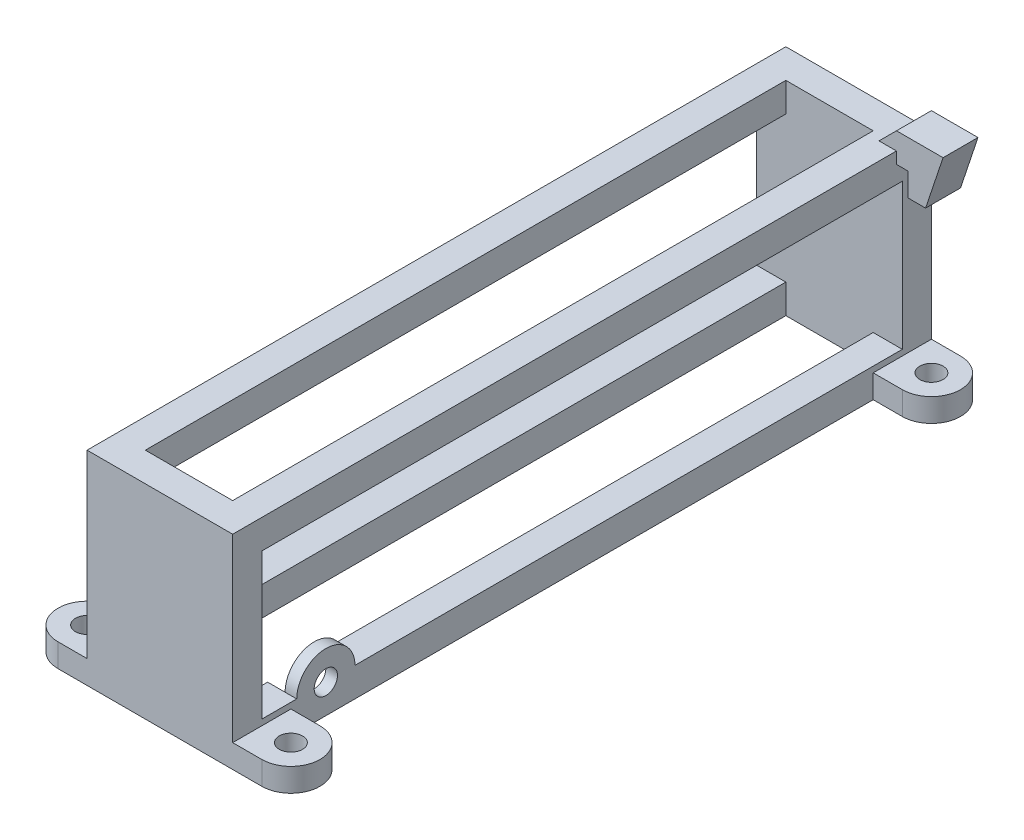
SolidWorks part; units mm, degrees
ref_plane "Front Plane" through (0, 0, 0) normal (0, 0, 1) x (1, 0, 0)
ref_plane "Top Plane" through (0, 0, 0) normal (0, 1, 0) x (1, 0, 0)
ref_plane "Right Plane" through (0, 0, 0) normal (1, 0, 0) x (0, 0, -1)
sketch "Sketch1" plane through (0, 0, 0) normal (1, 0, 0) x (0, 0, -1)
  line L1 (0, 0) -> (120, 0)
  line L2 (0, 0) -> (0, -35)
  line L3 (0, -35) -> (120, -35)
  line L4 (120, 0) -> (120, -35)
  line L5 (5, -30) -> (115, -30)
  line L6 (5, -30) -> (5, -5)
  line L7 (5, -5) -> (115, -5)
  line L8 (115, -30) -> (115, -5)
  dimension "D1" = 35
  dimension "D2" = 120
  dimension "D3" = 5
  dimension "D4" = 5
  dimension "D5" = 5
  dimension "D6" = 5
extrude "Boss-Extrude1" add sketch "Sketch1" along normal blind 25 contours L4 L1 L2 L3 L8 L5 L6 L7
sketch "Sketch2" plane through (0, -35, 0) normal (0, -1, 0) x (-1, 0, 0)
  line L0 (0, 120) -> (-25, 120) construction
  line L1 (-5, 115) -> (-20, 115)
  line L2 (-5, 115) -> (-5, 5)
  line L3 (-5, 5) -> (-20, 5)
  line L4 (-20, 115) -> (-20, 5)
  line L7 (0, 0) -> (-25, 0) construction
  line L8 (0, 0) -> (0, 120) construction
  line L9 (-25, 0) -> (-25, 120) construction
  dimension "D1" = 5
  dimension "D2" = 5
  dimension "D3" = 5
  dimension "D4" = 5
extrude "Cut-Extrude1" cut sketch "Sketch2" against normal up to surface (35 mm away) up to face at (12.5, 0, -60)
sketch "Sketch3" plane through (0, -35, 0) normal (0, -1, 0) x (1, 0, 0)
  line L0 (0, -120) -> (-5, -120)
  line L1 (-5, -110) -> (0, -110)
  line L2 (0, 0) -> (0, -120) construction
  line L3 (0, -110) -> (0, -120)
  line L4 (0, 0) -> (-5, 0)
  line L5 (-5, -10) -> (0, -10)
  line L6 (25, -120) -> (30, -120)
  line L7 (25, -110) -> (30, -110)
  line L8 (25, 0) -> (25, -120) construction
  line L9 (25, 0) -> (30, 0)
  line L10 (25, -10) -> (30, -10)
  line L11 (0, 0) -> (0, -10)
  line L12 (25, -10) -> (25, 0)
  line L13 (25, -110) -> (25, -120)
  arc A0 (-5, -120) -> (-5, -110) centre (-5, -115) cw
  circle A1 centre (-5, -115) radius 2
  arc A2 (-5, 0) -> (-5, -10) centre (-5, -5) ccw
  circle A3 centre (-5, -5) radius 2
  arc A4 (30, -110) -> (30, -120) centre (30, -115) cw
  circle A5 centre (30, -115) radius 2
  arc A6 (30, -10) -> (30, 0) centre (30, -5) ccw
  circle A7 centre (30, -5) radius 2
  dimension "D3" = 4
  dimension "D5" = 4
  dimension "D8" = 4
  dimension "D9" = 4
  dimension "D1" = 5
  dimension "D2" = 10
  dimension "D4" = 10
  dimension "D6" = 5
  dimension "D7" = 5
extrude "Boss-Extrude2" add sketch "Sketch3" against normal blind 4
sketch "Sketch4" plane through (20, 0, 0) normal (-1, 0, 0) x (0, 0, 1)
  line L0 (-5, -30) -> (-115, -30) construction
  line L1 (-11, -30) -> (-21, -30)
  line L2 (-11, -30) -> (-11, -35)
  line L3 (-11, -35) -> (-21, -35)
  line L4 (-21, -30) -> (-21, -35)
  line L5 (-115, -35) -> (-5, -35) construction
  line L6 (-5, -30) -> (-5, -35) construction
  dimension "D1" = 10
  dimension "D2" = 6
extrude "Cut-Extrude2" cut sketch "Sketch4" against normal blind 3
sketch "Sketch5" plane through (23, 0, 0) normal (-1, 0, 0) x (0, 0, 1)
  line L0 (-11, -30) -> (-21, -30)
  arc A0 (-21, -30) -> (-11, -30) centre (-16, -30) cw
extrude "Boss-Extrude3" add sketch "Sketch5" against normal blind 2
sketch "Sketch6" plane through (23, 0, 0) normal (-1, 0, 0) x (0, 0, 1)
  line L0 (-11, -30) -> (-21, -30) construction
  line L1 (-21, -30) -> (-21, -35) construction
  arc A0 (-11, -30) -> (-21, -30) centre (-16, -30) ccw construction
  circle A1 centre (-16, -30) radius 2
  dimension "D1" = 4
extrude "Cut-Extrude3" cut sketch "Sketch6" against normal up to surface (2 mm away) up to face at (25, -24.25, -60)
sketch "Sketch7" plane through (0, 0, -120) normal (0, 0, -1) x (-1, 0, 0)
  line L0 (-25, -2) -> (-27, -2)
  line L1 (-25, 0) -> (-25, -31) construction
  line L2 (-27, -2) -> (-27, -6)
  line L3 (-27, -6) -> (-30, -6)
  line L4 (-30, -6) -> (-33, 3)
  line L5 (-33, 3) -> (-25, 3)
  line L6 (-25, 3) -> (-25, 0)
  line L7 (-25, 3) -> (-22, 0)
  line L8 (-25, 0) -> (0, 0) construction
  line L9 (-22, 0) -> (-25, 0)
  line L10 (-25, 0) -> (-25, -2)
  line M9 (0, 0) -> (-25, 0)
  line M10 (-25, 0) -> (-25, -31)
  dimension "D1" = 2
  dimension "D2" = 2
  dimension "D3" = 4
  dimension "D4" = 3
  dimension "D5" = 8
  dimension "D6" = 3
  dimension "D7" = 3
extrude "Boss-Extrude4" add sketch "Sketch7" against normal blind 6 separate body contours L6 L5 L4 L3 L2 L0 M10 | L7 L6 M9
